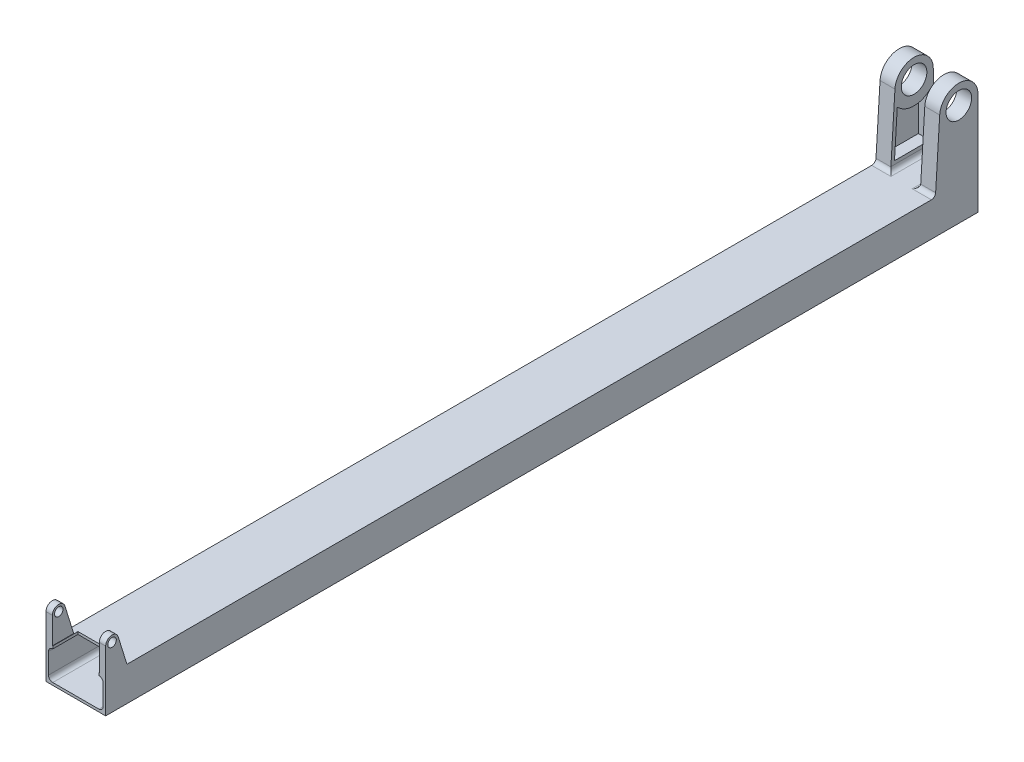
SolidWorks part; units mm, degrees
material "AISI 1045 Steel, cold drawn"
ref_plane "Front Plane" through (0, 0, 0) normal (0, 0, 1) x (1, 0, 0)
ref_plane "Top Plane" through (0, 0, 0) normal (0, 1, 0) x (1, 0, 0)
ref_plane "Right Plane" through (0, 0, 0) normal (1, 0, 0) x (0, 0, -1)
sketch "Sketch1" plane through (0, 0, 0) normal (1, 0, 0) x (0, 0, -1)
  line L0 (0, 0) -> (-2600, 0)
  line L1 (-2600, 0) -> (-2600, 101.6)
  line L2 (-2600, 101.6) -> (0, 101.6)
  line L3 (0, 101.6) -> (0, 0)
  line L4 (0, 101.6) -> (0, 304.8)
  line L5 (-114.1906, 308.3343) -> (-127, 101.6)
  arc A0 (0, 304.8) -> (-114.1906, 308.3343) centre (-57.15, 304.8) ccw
  circle A1 centre (-57.15, 304.8) radius 38.1
  dimension "D1" = 101.6
  dimension "D4" = 76.2
  dimension "D2" = 2600
  dimension "D3" = 203.2
  dimension "D5" = 19.05
  dimension "D6" = 69.85
sketch "Sketch2" plane through (0, 0, 0) normal (0, 0, 1) x (1, 0, 0)
  line L0 (0, 101.6) -> (0, 0) construction
  line L1 (0, 101.6) -> (-177.8, 101.6)
  line L2 (0, 101.6) -> (0, 0)
  line L3 (0, 0) -> (-177.8, 0)
  line L4 (-177.8, 101.6) -> (-177.8, 0)
  line L5 (0, 101.6) -> (0, 304.8) construction
  line L6 (-7.5, 94.1) -> (-7.5, 7.5)
  line L7 (-7.5, 7.5) -> (-170.3, 7.5)
  line L8 (-170.3, 94.1) -> (-170.3, 7.5)
  line L9 (-7.5, 94.1) -> (-170.3, 94.1)
  dimension "D1" = 101.6
  dimension "D2" = 177.8
  dimension "D3" = 7.5
extrude "Boss-Extrude2" add sketch "Sketch2" along normal up to vertex (2600 mm away) up to point (0, 101.6, 2600)
extrude "Boss-Extrude3" add sketch "Sketch1" against normal blind 44.45 contours L4 A0 L5 L2 A1
ref_plane "Plane1" through (-177.8, 0, 0) normal (-1, 0, 0) x (0, 0, 1)
sketch "Sketch3" plane through (-177.8, 0, 0) normal (-1, 0, 0) x (0, 0, 1)
  line L3 (0, 304.8) -> (0, 101.6)
  line L4 (0, 101.6) -> (127, 101.6)
  line L5 (127, 101.6) -> (114.1906, 308.3343)
  line L6 (0, 304.8) -> (0, 101.6)
  line L7 (0, 101.6) -> (127, 101.6)
  line L8 (127, 101.6) -> (114.1906, 308.3343)
  circle A0 centre (57.15, 304.8) radius 38.1 construction
  arc A1 (114.1906, 308.3343) -> (0, 304.8) centre (57.15, 304.8) ccw
  arc A2 (114.1906, 308.3343) -> (0, 304.8) centre (57.15, 304.8) ccw
  circle A3 centre (57.15, 304.8) radius 38.1
  dimension "D1" = 0
extrude "Boss-Extrude5" add sketch "Sketch3" against normal blind 44.45
fillet "Fillet1" radius 12.7 4 edges at (-7.5, 7.5, 1300) (-7.5, 94.1, 1300) (-170.3, 94.1, 1300) (-170.3, 7.5, 1300)
fillet "Fillet2" radius 12.7 4 edges at (-155.575, 101.6, 127) (-22.225, 101.6, 127) (-133.35, 101.6, 63.5) (-44.45, 101.6, 63.5)
sketch "Sketch5" plane through (0, 0, 0) normal (1, 0, 0) x (0, 0, -1)
  line L0 (-2600, 101.6) -> (-2600, 180.34)
  line L1 (-2562.7601, 185.9996) -> (-2536.5, 101.6)
  line L2 (-2600, 101.6) -> (-138.9375, 101.6) construction
  line L3 (-2536.5, 101.6) -> (-2600, 101.6)
  arc A0 (-2600, 180.34) -> (-2562.7601, 185.9996) centre (-2580.95, 180.34) cw
  circle A1 centre (-2580.95, 180.34) radius 12.7
  dimension "D3" = 6.35
  dimension "D4" = 25.4
  dimension "D1" = 78.74
  dimension "D2" = 63.5
extrude "Boss-Extrude7" add sketch "Sketch5" against normal blind 19.05
sketch "Sketch7" plane through (0, 0, 2600) normal (0, 0, 1) x (1, 0, 0)
  line L0 (-177.8, 101.6) -> (0, 101.6) construction
  point P4 (-88.9, 101.6)
ref_plane "Plane3" through (-88.9, 0, 0) normal (-1, 0, 0) x (0, 0, 1)
mirror "Mirror1" about plane through (-88.9, 0, 0) normal (-1, 0, 0) of "Boss-Extrude7"
sketch "Sketch8" plane through (-133.35, 0, 0) normal (1, 0, 0) x (0, 0, -1)
  line L3 (-114.1906, 308.3343) -> (-126.2131, 114.3)
  line L4 (-126.2131, 114.3) -> (0, 114.3)
  line L5 (0, 114.3) -> (0, 304.8)
  line L6 (-114.1906, 308.3343) -> (-126.2131, 114.3)
  line L7 (-126.2131, 114.3) -> (0, 114.3)
  line L8 (0, 114.3) -> (0, 304.8)
  line L12 (-104.2098, 307.7159) -> (-115.5743, 124.3)
  line L13 (-115.5743, 124.3) -> (-10, 124.3)
  line L14 (-10, 124.3) -> (-10, 304.8)
  line L15 (-104.2098, 307.7159) -> (-115.5743, 124.3)
  line L16 (-115.5743, 124.3) -> (-10, 124.3)
  line L17 (-10, 124.3) -> (-10, 304.8)
  arc A1 (0, 304.8) -> (-114.1906, 308.3343) centre (-57.15, 304.8) ccw
  arc A2 (0, 304.8) -> (-114.1906, 308.3343) centre (-57.15, 304.8) ccw
  arc A4 (-10, 304.8) -> (-104.2098, 307.7159) centre (-57.15, 304.8) ccw
  arc A5 (-10, 304.8) -> (-104.2098, 307.7159) centre (-57.15, 304.8) ccw
  circle A7 centre (-57.15, 304.8) radius 68.1
  circle A8 centre (-57.15, 304.8) radius 68.1
  dimension "D1" = 0
  dimension "D2" = 10
  dimension "D3" = 30
extrude "Cut-Extrude1" cut sketch "Sketch8" against normal offset from surface (34.45 mm away) 10 contours A8 L15 L16 L17 up to face at (-177.8, 151.6708, 1186.3343)
sketch "Sketch9" plane through (0, 101.6, 0) normal (0, 1, 0) x (1, 0, 0)
  line L0 (-57.15, 0) -> (-120.65, 0) construction
  line L1 (-88.9, 0) -> (0, 0)
  line L2 (-88.9, 0) -> (-88.9, -2600)
  line L3 (-88.9, -2600) -> (0, -2600)
  line L4 (0, 0) -> (0, -2600)
extrude "Cut-Extrude2" cut sketch "Sketch9" against normal through all both and the other way through all
mirror "Mirror2" about plane through (-88.9, 0, 0) normal (-1, 0, 0) of bodies 111
sketch "Sketch10" plane through (0, 94.1, 0) normal (0, -1, 0) x (1, 0, 0)
  line L0 (-157.6, 2525) -> (-20.2, 2525)
  line L4 (-157.6, 0) -> (-20.2, 0)
  line L5 (-20.2, 0) -> (-20.2, 2600)
  line L6 (-20.2, 2600) -> (-157.6, 2600)
  line L7 (-157.6, 2600) -> (-157.6, 0)
  line L8 (-157.6, 0) -> (-20.2, 0)
  line L9 (-20.2, 0) -> (-20.2, 2600)
  line L10 (-20.2, 2600) -> (-157.6, 2600)
  line L11 (-157.6, 2600) -> (-157.6, 0)
  line M7 (-20.2, 0) -> (-20.2, 2600)
  line M8 (-20.2, 2600) -> (-157.6, 2600)
  line M9 (-157.6, 2600) -> (-157.6, 0)
  dimension "D2" = 75
  dimension "D1" = 0
extrude "Cut-Extrude3" cut sketch "Sketch10" against normal blind 10 contours L0 M9 M7 M8
equation "\"D1@Sketch2\"=\"D1@Sketch1\""
